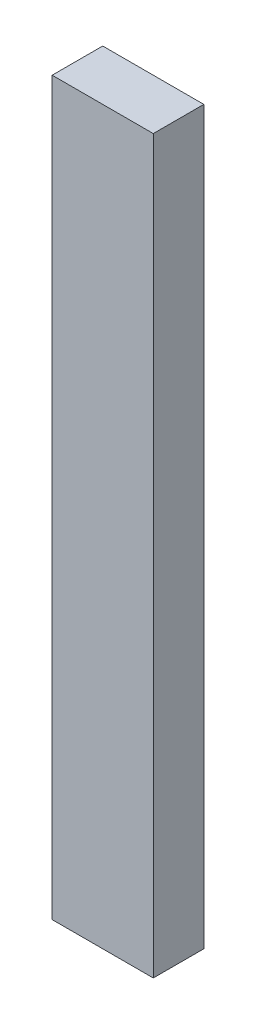
SolidWorks part; units mm, degrees
ref_plane "Front Plane" through (0, 0, 0) normal (0, 0, 1) x (1, 0, 0)
ref_plane "Top Plane" through (0, 0, 0) normal (0, 1, 0) x (1, 0, 0)
ref_plane "Right Plane" through (0, 0, 0) normal (1, 0, 0) x (0, 0, -1)
sketch "Sketch1" plane through (0, 0, 0) normal (0, 1, 0) x (1, 0, 0)
  line L1 (-40.1688, 6.8766) -> (-10.1688, 6.8766)
  line L2 (-40.1688, 6.8766) -> (-40.1688, -8.1234)
  line L3 (-40.1688, -8.1234) -> (-10.1688, -8.1234)
  line L4 (-10.1688, 6.8766) -> (-10.1688, -8.1234)
  dimension "D1" = 30
  dimension "D2" = 15
extrude "Boss-Extrude1" add sketch "Sketch1" along normal blind 217
